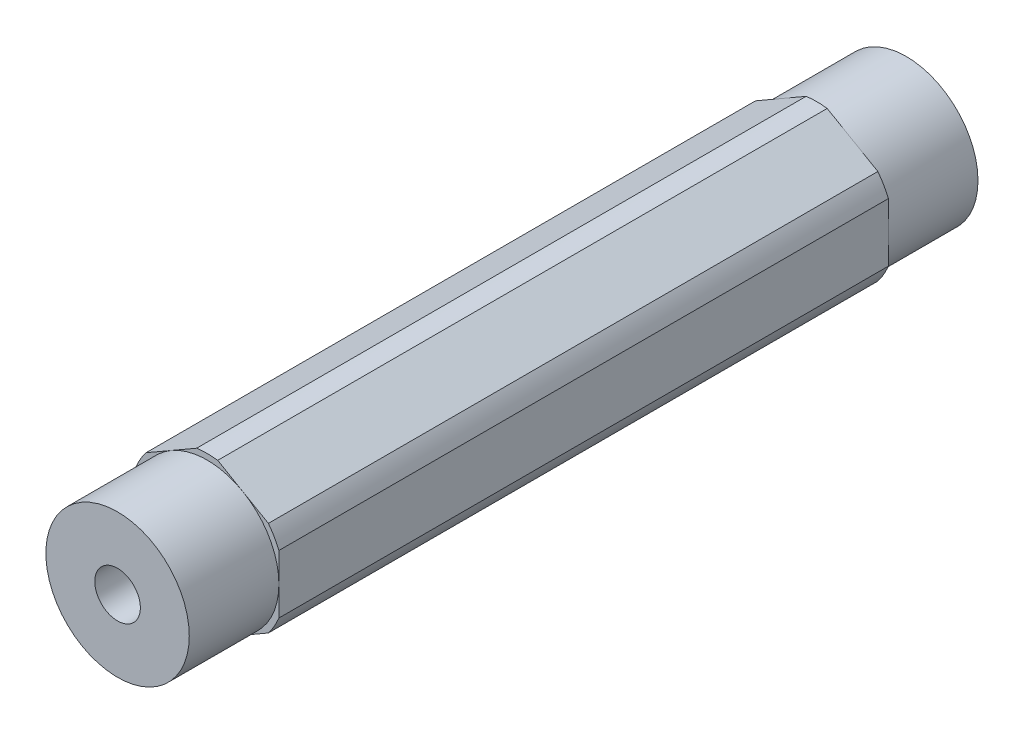
SolidWorks part; units mm, degrees
ref_plane "Front Plane" through (0, 0, 0) normal (0, 0, 1) x (1, 0, 0)
ref_plane "Top Plane" through (0, 0, 0) normal (0, 1, 0) x (1, 0, 0)
ref_plane "Right Plane" through (0, 0, 0) normal (1, 0, 0) x (0, 0, -1)
sketch "Sketch1" plane through (0, 0, 0) normal (0, 0, 1) x (1, 0, 0)
  line L1 (0, 7.3323) -> (-6.35, 3.6662)
  line L2 (-6.35, 3.6662) -> (-6.35, -3.6662)
  line L3 (-6.35, -3.6662) -> (0, -7.3323)
  line L4 (0, -7.3323) -> (6.35, -3.6662)
  line L5 (6.35, -3.6662) -> (6.35, 3.6662)
  line L6 (6.35, 3.6662) -> (0, 7.3323)
  circle A0 centre (0, 0) radius 6.35 construction
  circle A1 centre (0, 0) radius 6.858
  circle A2 centre (0, 0) radius 2.0193
  dimension "D1" = 12.7
  dimension "D2" = 13.716
  dimension "D3" = 4.0386
extrude "Boss-Extrude1" add sketch "Sketch1" along normal mid plane 53.975 contours L5 A1 L6 L1 L2 L3 L4
sketch "Sketch2" plane through (0, 0, 26.9875) normal (0, 0, 1) x (1, 0, 0)
  circle A0 centre (0, 0) radius 6.35
  circle A1 centre (0, 0) radius 2.0193
  dimension "D1" = 12.7
  dimension "D2" = 4.0386
extrude "Boss-Extrude2" add sketch "Sketch2" along normal blind 7.9375
mirror "Mirror1" about plane through (0, 0, 0) normal (0, 0, 1) of "Boss-Extrude2"
